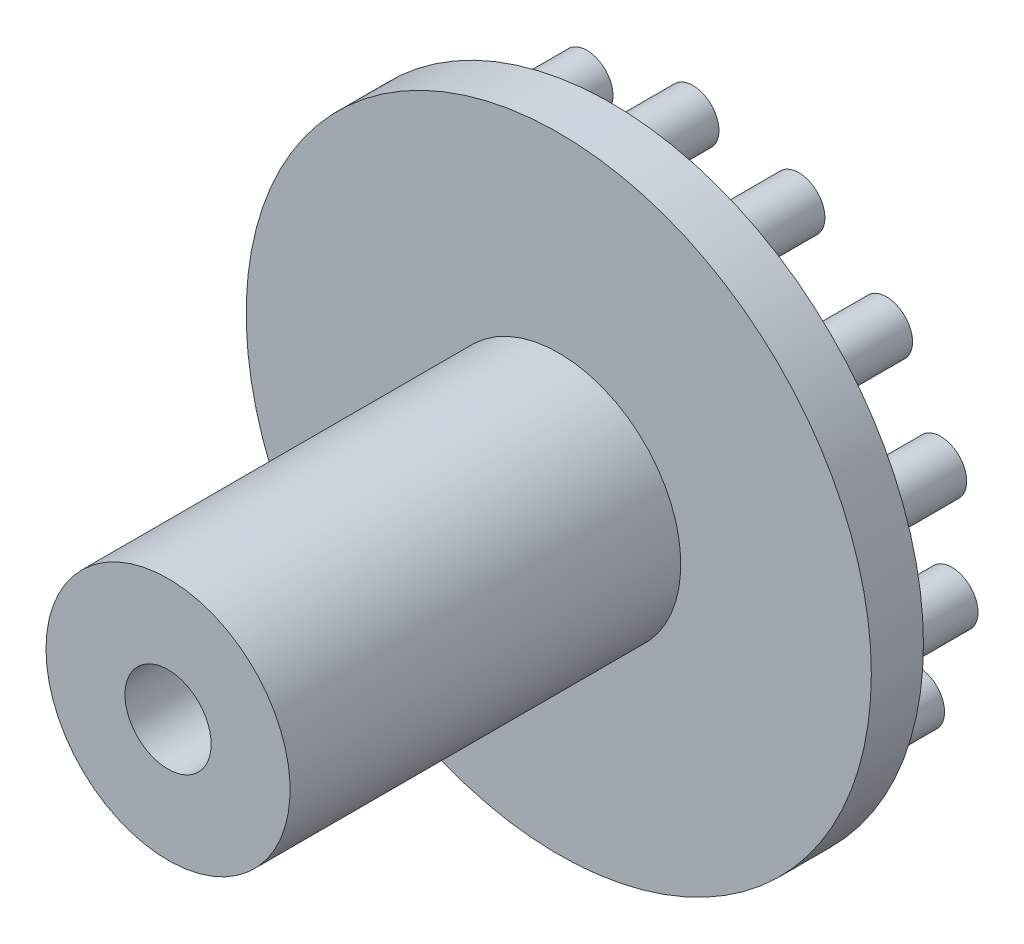
SolidWorks part; units mm, degrees
material "ABS"
ref_plane "Front Plane" through (0, 0, 0) normal (0, 0, 1) x (1, 0, 0)
ref_plane "Top Plane" through (0, 0, 0) normal (0, 1, 0) x (1, 0, 0)
ref_plane "Right Plane" through (0, 0, 0) normal (1, 0, 0) x (0, 0, -1)
sketch "Sketch1" plane through (0, 0, 0) normal (0, 0, 1) x (1, 0, 0)
  circle A0 centre (0, 0) radius 4.55
  circle A1 centre (0, 0) radius 15.24
  dimension "D1" = 9.1
  dimension "D2" = 30.48
extrude "Boss-Extrude1" add sketch "Sketch1" along normal blind 2.54
sketch "Sketch2" plane through (0, 0, 2.54) normal (0, 0, 1) x (1, 0, 0)
  circle A0 centre (0, 0) radius 5.95
  dimension "D1" = 11.9
extrude "Boss-Extrude2" add sketch "Sketch2" along normal blind 19.05
sketch "Sketch3" plane through (0, 0, 21.59) normal (0, 0, 1) x (1, 0, 0)
  line L1 (3.6662, 6.35) -> (-3.6662, 6.35)
  line L2 (-3.6662, 6.35) -> (-7.3323, 0)
  line L3 (-7.3323, 0) -> (-3.6662, -6.35)
  line L4 (-3.6662, -6.35) -> (3.6662, -6.35)
  line L5 (3.6662, -6.35) -> (7.3323, 0)
  line L6 (7.3323, 0) -> (3.6662, 6.35)
  circle A1 centre (0, 0) radius 6.35 construction
  dimension "D1" = 12.7
extrude "Boss-Extrude3" [suppressed] add sketch "Sketch3" along normal blind 38.1
sketch "Sketch4" [suppressed] plane through (0, 0, 47.64) normal (0, 0, 1) x (1, 0, 0)
  line L1 (-0.635, 1.905) -> (0.635, 1.905)
  line L2 (-0.635, 1.905) -> (-0.635, 4.445)
  line L3 (-0.635, 4.445) -> (0.635, 4.445)
  line L4 (0.635, 1.905) -> (0.635, 4.445)
  point P4 (0, 1.905)
  dimension "D1" = 2.54
  dimension "D2" = 1.905
  dimension "D3" = 1.27
extrude "Boss-Extrude4" [suppressed] add sketch "Sketch4" against normal blind 2.54
sketch "Sketch5" plane through (0, 0, 0) normal (0, 0, -1) x (-1, 0, 0)
  line L0 (0, 0) -> (0, 12.7) construction
  circle A0 centre (0, 12.7) radius 1.27
  circle A13 centre (5.1656, 11.602) radius 1.27
  circle A14 centre (9.4379, 8.498) radius 1.27
  circle A15 centre (12.0784, 3.9245) radius 1.27
  circle A16 centre (12.6304, -1.3275) radius 1.27
  circle A17 centre (10.9985, -6.35) radius 1.27
  circle A18 centre (7.4649, -10.2745) radius 1.27
  circle A19 centre (2.6405, -12.4225) radius 1.27
  circle A20 centre (-2.6405, -12.4225) radius 1.27
  circle A21 centre (-7.4649, -10.2745) radius 1.27
  circle A22 centre (-10.9985, -6.35) radius 1.27
  circle A23 centre (-12.6304, -1.3275) radius 1.27
  circle A24 centre (-12.0784, 3.9245) radius 1.27
  circle A25 centre (-9.4379, 8.498) radius 1.27
  circle A26 centre (-5.1656, 11.602) radius 1.27
  dimension "D2" = 2.54
  dimension "D1" = 12.7
  dimension "D3" = 15
  dimension "D4" = 12.7
extrude "Boss-Extrude5" add sketch "Sketch5" along normal blind 4
sketch "Sketch6" plane through (0, 0, 21.59) normal (0, 0, 1) x (1, 0, 0)
  circle A1 centre (0, 0) radius 5.95
  circle A2 centre (0, 0) radius 5.95
  point P1 (0, 0)
  dimension "D1" = 0
hole_wizard "M5x0.8 Tapped Hole2" positions "Sketch6" profile "Sketch7" tap size "M5x0.8" standard "ANSI Metric" end condition through all
cosmetic thread "Hole Thread1" parameters "D2"=5
sketch "Sketch7" plane through (0, 0, 21.59) normal (1, 0, 0) x (0, -1, 0)
  line L0 (0, 0) -> (0, 25.59)
  line L1 (0, 25.59) -> (2.1, 25.59)
  line L2 (2.1, 25.59) -> (2.1, 0)
  line L5 (2.1, 0) -> (0, 0)
  line L11 (0, -6.35) -> (0, 107.95) construction
  dimension "Thru Tap Drill Dia." = 4.2
  dimension "Thru Tap Drill Depth" = 25.59
